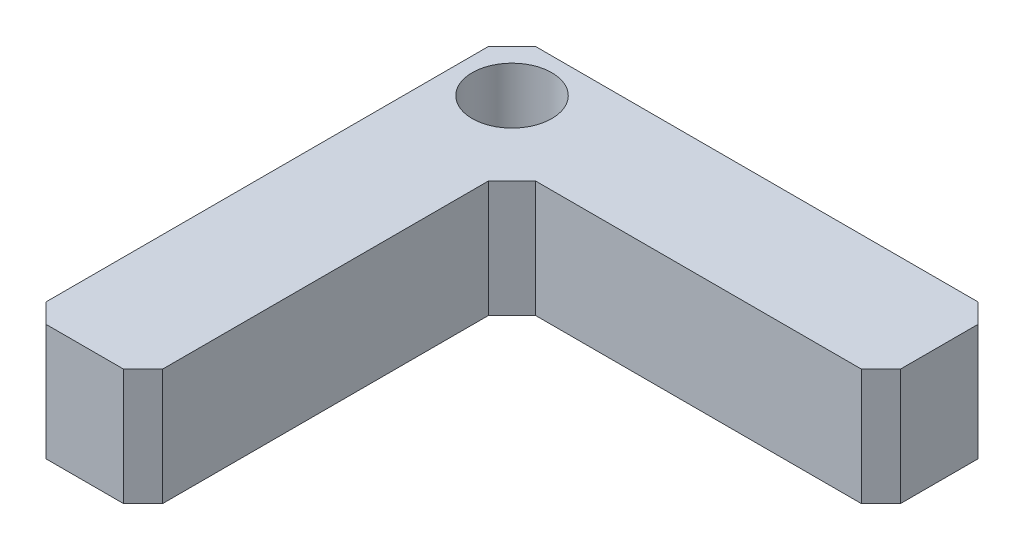
SolidWorks part; units mm, degrees
ref_plane "Front Plane" through (0, 0, 0) normal (0, 0, 1) x (1, 0, 0)
ref_plane "Top Plane" through (0, 0, 0) normal (0, 1, 0) x (1, 0, 0)
ref_plane "Right Plane" through (0, 0, 0) normal (1, 0, 0) x (0, 0, -1)
sketch "Sketch1" plane through (0, 0, 0) normal (0, 1, 0) x (1, 0, 0)
  line L25 (0, 0) -> (57, 0)
  line L26 (0, 0) -> (-3, -3)
  line L27 (-3, -3) -> (-3, -60)
  line L28 (57, 0) -> (59.5, -2.5)
  line L29 (59.5, -2.5) -> (59.5, -12.5)
  line L30 (59.5, -12.5) -> (57, -15)
  line L31 (57, -15) -> (14.9981, -15)
  line L32 (14.9981, -15) -> (12, -17.9981)
  line L33 (12, -17.9981) -> (12, -60)
  line L34 (12, -60) -> (9.5, -62.5)
  line L37 (-3, -60) -> (-0.5, -62.5)
  line L38 (-0.5, -62.5) -> (9.5, -62.5)
  circle A1 centre (4, -7) radius 5.125
  dimension "D25" = 10.25
  dimension "D13" = 3
  dimension "D14" = 3
  dimension "D15" = 2.5
  dimension "D16" = 62.5
  dimension "D17" = 15
  dimension "D18" = 2.5
  dimension "D19" = 2.5
  dimension "D20" = 15
  dimension "D21" = 62.5
  dimension "D22" = 2.5
  dimension "D23" = 2.5
  dimension "D24" = 4.24
  dimension "D26" = 7
  dimension "D27" = 7
extrude "Boss-Extrude1" add sketch "Sketch1" along normal blind 15 contours L37 L38 L34 L33 L32 L31 L30 L29 L28 L25 L26 L27 A1
